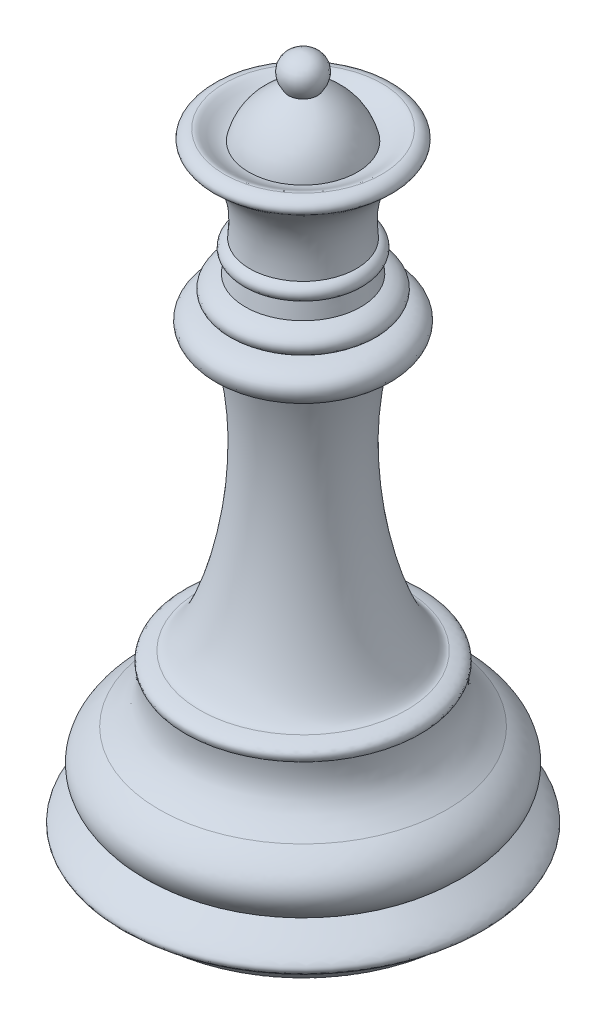
SolidWorks part; units mm, degrees
ref_plane "Front Plane" through (0, 0, 0) normal (0, 0, 1) x (1, 0, 0)
ref_plane "Top Plane" through (0, 0, 0) normal (0, 1, 0) x (1, 0, 0)
ref_plane "Right Plane" through (0, 0, 0) normal (1, 0, 0) x (0, 0, -1)
sketch "Sketch1" plane through (0, 0, 0) normal (0, 0, 1) x (1, 0, 0)
  line L0 (0, 0) -> (140.775, 0)
  line L1 (0, 718.3699) -> (0, 0)
  line L4 (66.6413, 464.7591) -> (78.186, 464.7591)
  line L5 (59.1915, 521.4253) -> (56.5132, 536.9951)
  spline S0 degree 3 poles (140.775, 0) (155.2341, 3.2317) (159.3779, 13.1584) (191.9118, 35.6986) (193.0489, 34.526) (155.2835, 59.9104) knots 0 0 0 0 0.222478 0.322478 1 1 1 1
  spline S1 degree 3 poles (155.2835, 59.9104) (182.1068, 81.6172) (174.957, 102.6888) (147.2931, 119.7662) knots 0 0 0 0 1 1 1 1
  spline S2 degree 3 poles (147.2931, 119.7662) (124.4339, 136.2568) (118.1249, 147.7502) (120.296, 173.4124) knots 0 0 0 0 1 1 1 1
  spline S3 degree 3 poles (120.296, 173.4124) (125.0049, 181.6266) (117.9942, 184.94) (105.8893, 187.2721) knots 0 0 0 0 1 1 1 1
  spline S4 degree 3 poles (78.186, 464.7591) (94.273, 464.5432) (107.8225, 494.4634) (66.0437, 496.8676) knots 0 0 0 0 1 1 1 1
  spline S5 degree 3 poles (66.0437, 496.8676) (81.5002, 502.3958) (81.8054, 516.0796) (59.1915, 521.4253) knots 0 0 0 0 1 1 1 1
  spline S6 degree 3 poles (56.5132, 536.9951) (65.7259, 541.8283) (63.0543, 550.693) (54.6745, 553.1102) knots 0 0 0 0 1 1 1 1
  spline S7 degree 3 poles (54.6745, 553.1102) (50.3665, 592.9597) (60.3652, 615.1453) (89.4966, 636.4592) knots 0 0 0 0 1 1 1 1
  spline S8 degree 3 poles (89.4966, 636.4592) (96.2905, 641.7154) (88.5648, 649.6237) (80.6888, 649.7878) knots 0 0 0 0 1 1 1 1
  spline S9 degree 3 poles (80.6888, 649.7878) (74.8074, 650.2121) (68.3715, 641.5141) (55.5793, 639.1305) knots 0 0 0 0 1 1 1 1
  spline S10 degree 2 poles (55.5793, 639.1305) (48.2567, 669.2884) (14.8257, 686.5976) knots 0 0 0 1 1 1
  spline S11 degree 3 poles (14.8257, 686.5976) (26.1493, 702.2285) (17.7402, 717.4002) (0, 718.3699) knots 0 0 0 0 1 1 1 1
  spline S12 degree 3 poles (66.6413, 464.7591) (30.6517, 340.5088) (82.8423, 188.466) (105.8893, 187.2721) knots 0 0 0 0 1 1 1 1
revolve "Revolve1" add sketch "Sketch1" angle 360 about L1
scale "Scale1" scale about origin uniform scaling yes scale factor 0.5
